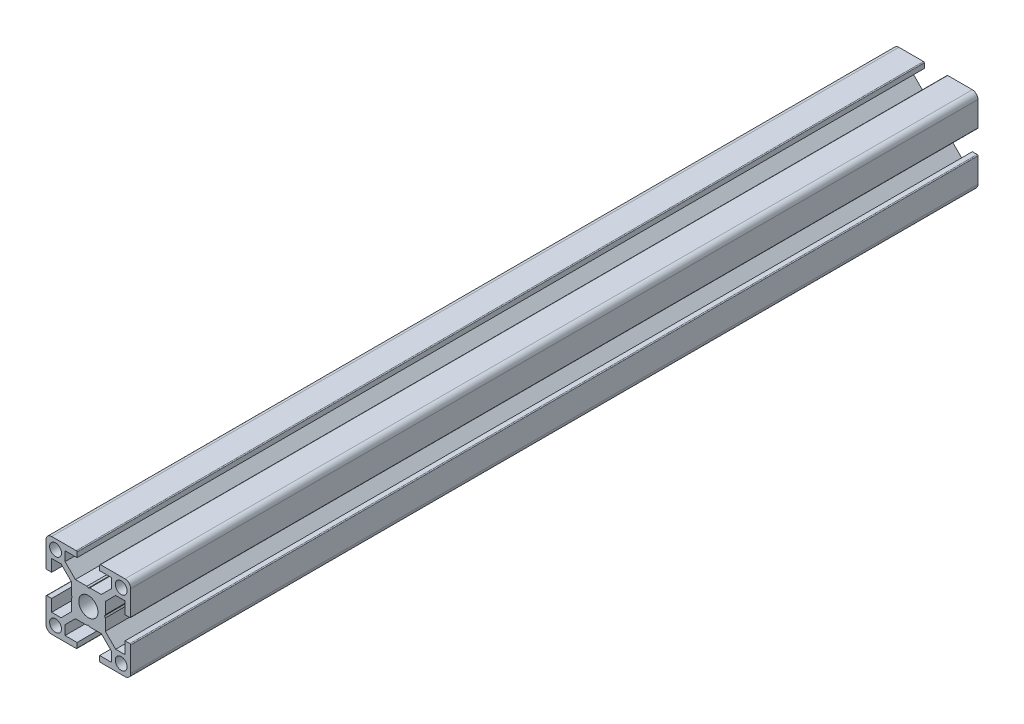
SolidWorks part; units mm, degrees
ref_plane "Front Plane" through (0, 0, 0) normal (0, 0, 1) x (1, 0, 0)
ref_plane "Top Plane" through (0, 0, 0) normal (0, 1, 0) x (1, 0, 0)
ref_plane "Right Plane" through (0, 0, 0) normal (1, 0, 0) x (0, 0, -1)
ref_plane "Plane1" through (0, 0, 0) normal (0, 0, 1) x (1, 0, 0)
sketch "Sketch1" plane through (0, 0, 0) normal (0, 0, 1) x (1, 0, 0)
  line L0 (-15, -4.3) -> (-15, -13)
  line L1 (-13, -15) -> (-4.3, -15)
  line L2 (-4, -14.7) -> (-4, -13)
  line L3 (-4, -13) -> (-8.25, -13)
  line L4 (-8.25, -13) -> (-8.25, -9.6642)
  line L5 (-8.25, -9.6642) -> (-4.5858, -6)
  line L6 (-4.5858, -6) -> (-0.5196, -6)
  line L7 (-0.5196, -6) -> (0, -5.7)
  line L8 (0, -5.7) -> (0.5196, -6)
  line L9 (0.5196, -6) -> (4.5858, -6)
  line L10 (4.5858, -6) -> (8.25, -9.6642)
  line L11 (8.25, -9.6642) -> (8.25, -13)
  line L12 (8.25, -13) -> (4, -13)
  line L13 (4, -13) -> (4, -14.7)
  line L14 (4.3, -15) -> (13, -15)
  line L15 (15, -13) -> (15, -4.3)
  line L16 (14.7, -4) -> (13, -4)
  line L17 (13, -4) -> (13, -8.25)
  line L18 (13, -8.25) -> (9.6642, -8.25)
  line L19 (9.6642, -8.25) -> (6, -4.5858)
  line L20 (6, -4.5858) -> (6, -0.5196)
  line L21 (6, -0.5196) -> (5.7, 0)
  line L22 (5.7, 0) -> (6, 0.5196)
  line L23 (6, 0.5196) -> (6, 4.5858)
  line L24 (6, 4.5858) -> (9.6642, 8.25)
  line L25 (9.6642, 8.25) -> (13, 8.25)
  line L26 (13, 8.25) -> (13, 4)
  line L27 (13, 4) -> (14.7, 4)
  line L28 (15, 4.3) -> (15, 13)
  line L29 (13, 15) -> (4.3, 15)
  line L30 (4, 14.7) -> (4, 13)
  line L31 (4, 13) -> (8.25, 13)
  line L32 (8.25, 13) -> (8.25, 9.6642)
  line L33 (8.25, 9.6642) -> (4.5858, 6)
  line L34 (4.5858, 6) -> (0.5196, 6)
  line L35 (0.5196, 6) -> (0, 5.7)
  line L36 (0, 5.7) -> (-0.5196, 6)
  line L37 (-0.5196, 6) -> (-4.5858, 6)
  line L38 (-4.5858, 6) -> (-8.25, 9.6642)
  line L39 (-8.25, 9.6642) -> (-8.25, 13)
  line L40 (-8.25, 13) -> (-4, 13)
  line L41 (-4, 13) -> (-4, 14.7)
  line L42 (-4.3, 15) -> (-13, 15)
  line L43 (-15, 13) -> (-15, 4.3)
  line L44 (-14.7, 4) -> (-13, 4)
  line L45 (-13, 4) -> (-13, 8.25)
  line L46 (-13, 8.25) -> (-9.6642, 8.25)
  line L47 (-9.6642, 8.25) -> (-6, 4.5858)
  line L48 (-6, 4.5858) -> (-6, 0.5196)
  line L49 (-6, 0.5196) -> (-5.7, 0)
  line L50 (-5.7, 0) -> (-6, -0.5196)
  line L51 (-6, -0.5196) -> (-6, -4.5858)
  line L52 (-6, -4.5858) -> (-9.6642, -8.25)
  line L53 (-9.6642, -8.25) -> (-13, -8.25)
  line L54 (-13, -8.25) -> (-13, -4)
  line L55 (-13, -4) -> (-14.7, -4)
  arc A0 (-15, -13) -> (-13, -15) centre (-13, -13) ccw
  arc A1 (-4.3, -15) -> (-4, -14.7) centre (-4.3, -14.7) ccw
  arc A2 (4, -14.7) -> (4.3, -15) centre (4.3, -14.7) ccw
  arc A3 (13, -15) -> (15, -13) centre (13, -13) ccw
  arc A4 (15, -4.3) -> (14.7, -4) centre (14.7, -4.3) ccw
  arc A5 (14.7, 4) -> (15, 4.3) centre (14.7, 4.3) ccw
  arc A6 (15, 13) -> (13, 15) centre (13, 13) ccw
  arc A7 (4.3, 15) -> (4, 14.7) centre (4.3, 14.7) ccw
  arc A8 (-4, 14.7) -> (-4.3, 15) centre (-4.3, 14.7) ccw
  arc A9 (-13, 15) -> (-15, 13) centre (-13, 13) ccw
  arc A10 (-15, 4.3) -> (-14.7, 4) centre (-14.7, 4.3) ccw
  arc A11 (-14.7, -4) -> (-15, -4.3) centre (-14.7, -4.3) ccw
  circle A12 centre (11.625, -11.625) radius 2.1
  circle A13 centre (11.625, 11.625) radius 2.1
  circle A14 centre (0, 0) radius 3.4
  circle A15 centre (-11.625, -11.625) radius 2.1
  circle A16 centre (-11.625, 11.625) radius 2.1
extrude "Boss-Extrude1" add sketch "Sketch1" against normal blind 300
